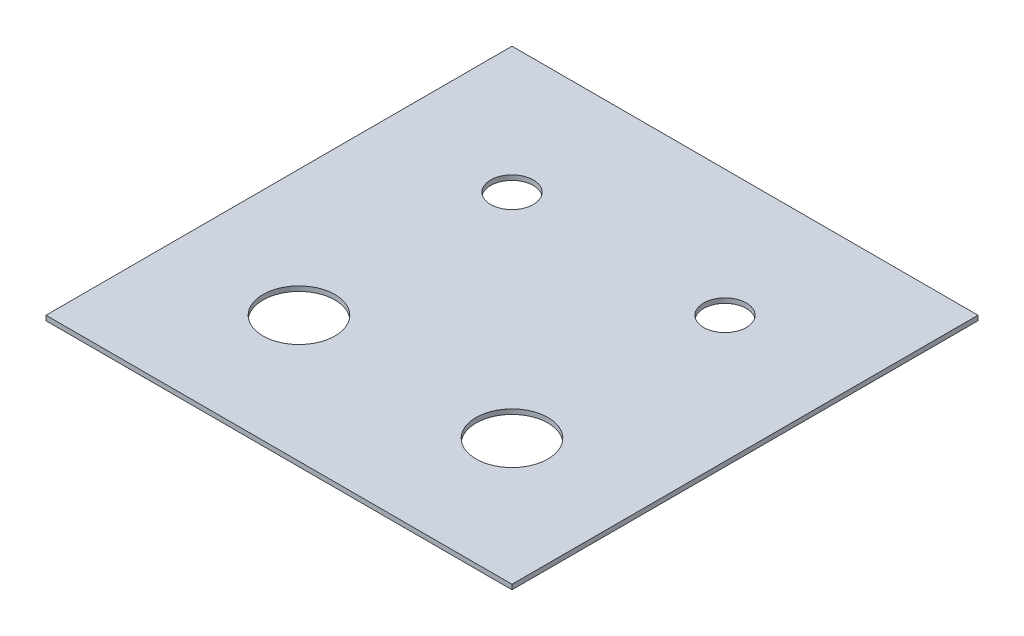
SolidWorks part; units mm, degrees
ref_plane "Front Plane" through (0, 0, 0) normal (0, 0, 1) x (1, 0, 0)
ref_plane "Top Plane" through (0, 0, 0) normal (0, 1, 0) x (1, 0, 0)
ref_plane "Right Plane" through (0, 0, 0) normal (1, 0, 0) x (0, 0, -1)
sketch "Sketch1" plane through (0, 0, 0) normal (0, 1, 0) x (1, 0, 0)
  line L0 (0, -22.225) -> (0, 22.225) construction
  line L1 (-22.225, 22.225) -> (22.225, 22.225)
  line L2 (-22.225, 22.225) -> (-22.225, -22.225)
  line L3 (-22.225, -22.225) -> (22.225, -22.225)
  line L4 (22.225, 22.225) -> (22.225, -22.225)
  line L5 (-22.225, 22.225) -> (22.225, -22.225) construction
  line L6 (-22.225, -22.225) -> (22.225, 22.225) construction
  circle A0 centre (-10.16, 10.16) radius 2.032
  circle A1 centre (10.16, 10.16) radius 2.032
  circle A2 centre (-10.16, -10.16) radius 3.429
  circle A3 centre (10.16, -10.16) radius 3.429
  point P0 (0, 0)
  dimension "D3" = 4.064
  dimension "D6" = 6.858
  dimension "D1" = 44.45
  dimension "D2" = 44.45
  dimension "D4" = 10.16
  dimension "D5" = 10.16
extrude "Boss-Extrude1" add sketch "Sketch1" along normal blind 0.46 contours L1 L4 L3 L2
